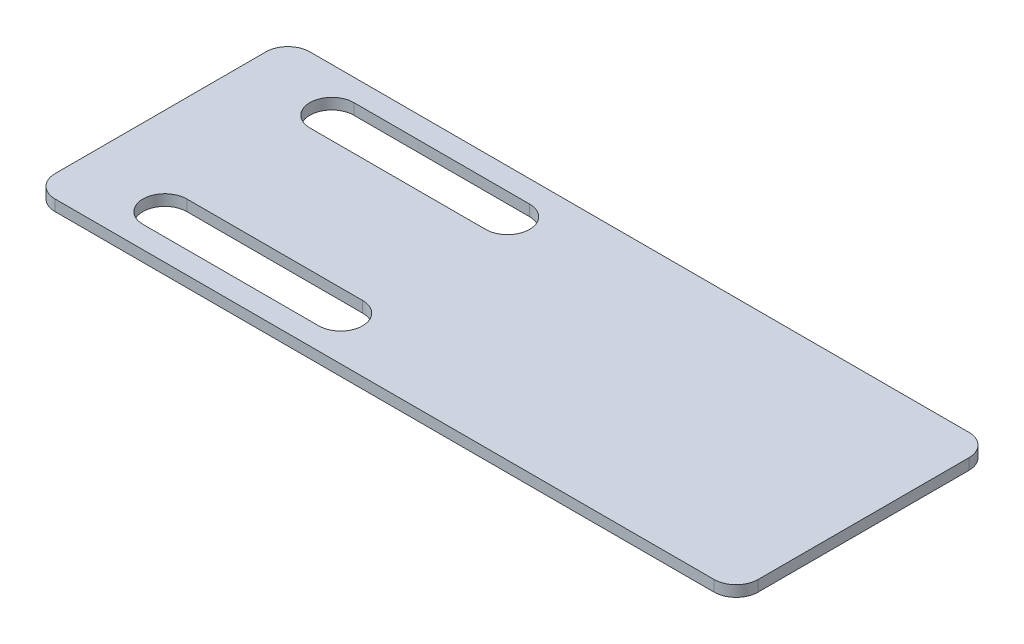
SolidWorks part; units mm, degrees
ref_plane "Front Plane" through (0, 0, 0) normal (0, 0, 1) x (1, 0, 0)
ref_plane "Top Plane" through (0, 0, 0) normal (0, 1, 0) x (1, 0, 0)
ref_plane "Right Plane" through (0, 0, 0) normal (1, 0, 0) x (0, 0, -1)
sketch "Sketch1" plane through (0, 0, 0) normal (0, 1, 0) x (1, 0, 0)
  line L0 (-76.2, -24.13) -> (-25.4, -24.13) construction
  line L1 (-101.6, 36.83) -> (101.6, 36.83)
  line L2 (-101.6, 36.83) -> (-101.6, -36.83)
  line L3 (-101.6, -36.83) -> (101.6, -36.83)
  line L4 (101.6, 36.83) -> (101.6, -36.83)
  line L5 (-101.6, 0) -> (0, 0) construction
  line L6 (-50.8, 0) -> (-50.8, -36.83) construction
  line L7 (-76.2, -17.78) -> (-25.4, -17.78)
  line L8 (-76.2, -30.48) -> (-25.4, -30.48)
  line L9 (-76.2, 24.13) -> (-25.4, 24.13) construction
  line L10 (-76.2, 17.78) -> (-25.4, 17.78)
  line L11 (-76.2, 30.48) -> (-25.4, 30.48)
  arc A0 (-76.2, -17.78) -> (-76.2, -30.48) centre (-76.2, -24.13) ccw
  arc A1 (-25.4, -30.48) -> (-25.4, -17.78) centre (-25.4, -24.13) ccw
  arc A2 (-76.2, 17.78) -> (-76.2, 30.48) centre (-76.2, 24.13) cw
  arc A3 (-25.4, 30.48) -> (-25.4, 17.78) centre (-25.4, 24.13) cw
  point P0 (0, 0)
  point P8 (-50.8, -24.13)
  point P13 (101.6, 0)
  point P14 (-101.6, 0)
  point P15 (0, 36.83)
  point P16 (0, -36.83)
  point P21 (-79.0926, -30.48)
  point P22 (-34.171, -18.415)
  point P25 (-50.8, 24.13)
  point P30 (0, 0)
  dimension "D4" = 6.35
  dimension "D1" = 73.66
  dimension "D2" = 203.2
  dimension "D3" = 50.8
  dimension "D5" = 12.7
extrude "Boss-Extrude1" add sketch "Sketch1" along normal blind 3.175
fillet "Fillet1" radius 6.35 4 edges at (-101.6, 1.5875, 36.83) (-101.6, 1.5875, -36.83) (101.6, 1.5875, -36.83) (101.6, 1.5875, 36.83)
